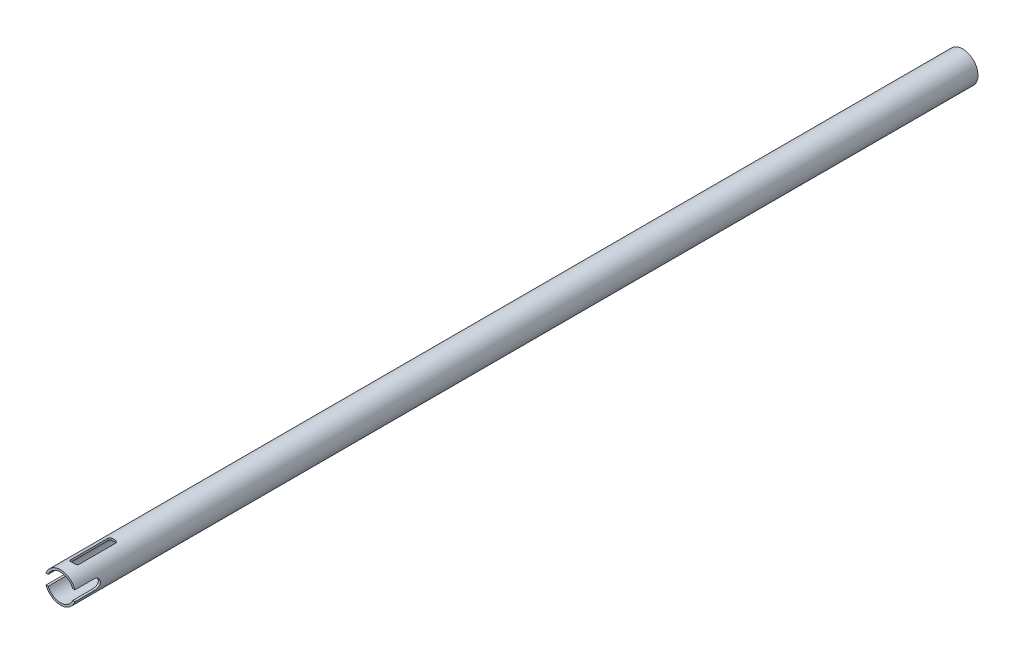
SolidWorks part; units mm, degrees
ref_plane "Front Plane" through (0, 0, 0) normal (0, 0, 1) x (1, 0, 0)
ref_plane "Top Plane" through (0, 0, 0) normal (0, 1, 0) x (1, 0, 0)
ref_plane "Right Plane" through (0, 0, 0) normal (1, 0, 0) x (0, 0, -1)
sketch "Sketch1" plane through (0, 0, 0) normal (0, 0, 1) x (1, 0, 0)
  circle A0 centre (0, 0) radius 4.7625
  circle A1 centre (0, 0) radius 4.1275
  dimension "D1" = 9.525
  dimension "D2" = 8.255
extrude "ShaftBody" add sketch "Sketch1" against normal blind 280
sketch "Sketch6" plane through (0, 0, 0) normal (1, 0, 0) x (0, 0, -1)
  line L1 (6.0325, 1.5875) -> (0, 1.5875)
  line L2 (6.0325, 1.5875) -> (6.0325, -1.5875) construction
  line L3 (6.0325, -1.5875) -> (0, -1.5875)
  line L4 (0, 1.5875) -> (0, -1.5875)
  arc A0 (6.0325, -1.5875) -> (6.0325, 1.5875) centre (6.0325, 0) ccw
  dimension "D1" = 3.175
  dimension "D2" = 6.0325
extrude "SideCuts" cut sketch "Sketch6" against normal through all and the other way through all
sketch "Sketch7" plane through (0, 0, 0) normal (0, 1, 0) x (1, 0, 0)
  line L0 (-4.4901, 0) -> (4.4901, 0) construction
  line L1 (-0.635, 3.81) -> (0.635, 3.81)
  line L2 (-1.27, 4.445) -> (-1.27, 15.875)
  line L3 (-0.635, 16.51) -> (0.635, 16.51)
  line L4 (1.27, 4.445) -> (1.27, 15.875)
  line L5 (-1.27, 3.81) -> (1.27, 16.51) construction
  line L6 (-1.27, 16.51) -> (1.27, 3.81) construction
  arc A0 (0.635, 3.81) -> (1.27, 4.445) centre (0.635, 4.445) ccw
  arc A1 (-0.635, 3.81) -> (-1.27, 4.445) centre (-0.635, 4.445) cw
  arc A2 (1.27, 15.875) -> (0.635, 16.51) centre (0.635, 15.875) ccw
  arc A3 (-0.635, 16.51) -> (-1.27, 15.875) centre (-0.635, 15.875) ccw
  point P0 (0, 10.16)
  dimension "D4" = 0.635
  dimension "D1" = 2.54
  dimension "D2" = 3.81
  dimension "D3" = 12.7
extrude "Cut-Extrude2" cut sketch "Sketch7" along normal up to next
